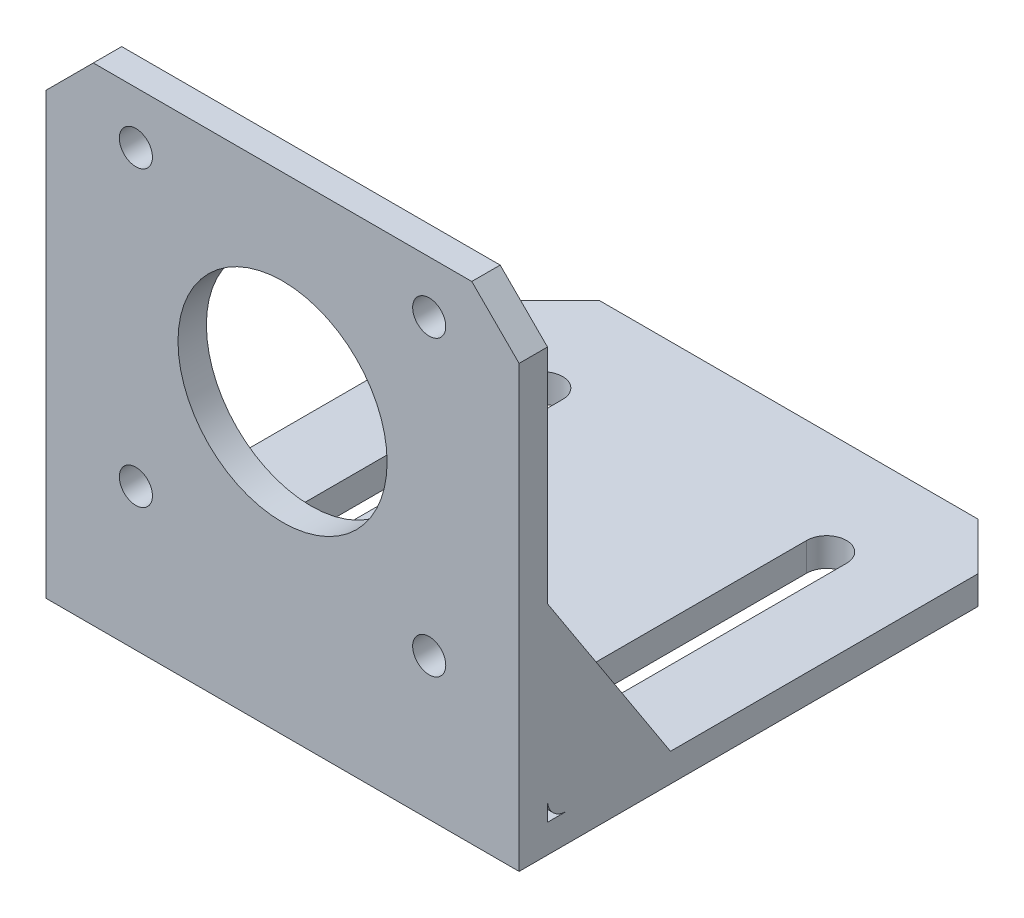
SolidWorks part; units mm, degrees
ref_plane "前视基准面" through (0, 0, 0) normal (0, 0, 1) x (1, 0, 0)
ref_plane "上视基准面" through (0, 0, 0) normal (0, 1, 0) x (1, 0, 0)
ref_plane "右视基准面" through (0, 0, 0) normal (1, 0, 0) x (0, 0, -1)
other "Configuration Table"
sketch "草图1" plane through (0, 0, 0) normal (1, 0, 0) x (0, 0, -1)
  line L0 (0, 0) -> (3, 0)
  line L1 (3, 0) -> (3, -48.5)
  line L2 (3, -48.5) -> (53.5, -48.5)
  line L3 (53.5, -48.5) -> (53.5, -51.5)
  line L4 (53.5, -51.5) -> (0, -51.5)
  line L5 (0, -51.5) -> (0, 0)
  dimension "D1" = 3
  dimension "D2" = 3
  dimension "D3" = 53.5
  dimension "D4" = 51.5
  dimension "D5" = 48.5
extrude "凸台-拉伸1" add sketch "草图1" along normal blind 50
sketch "草图2" plane through (0, 0, -3) normal (0, 0, -1) x (-1, 0, 0)
  line L0 (-50, 0) -> (0, 0) construction
  line L3 (-50, -48.5) -> (-50, 0) construction
  circle A0 centre (-25, -21) radius 11.05
  dimension "D1" = 22.1
  dimension "D2" = 21
  dimension "D3" = 25
extrude "切除-拉伸1" cut sketch "草图2" against normal through all
chamfer "倒角1" distance 5 angle 45 4 edges at (0, -50, -53.5) (50, -50, -53.5) (50, 0, -1.5) (0, 0, -1.5)
sketch "草图3" plane through (0, 0, -3) normal (0, 0, -1) x (-1, 0, 0)
  line L0 (-25, -21) -> (-25, 1.3621) construction
  line L1 (-40.5, -5.5) -> (-40.5, -45.4102) construction
  circle A0 centre (-40.5, -5.5) radius 1.75
  circle A1 centre (-9.5, -5.5) radius 1.75
  circle A2 centre (-9.5, -36.5) radius 1.75
  circle A3 centre (-40.5, -36.5) radius 1.75
  circle A4 centre (-25, -21) radius 21.9203 construction
  point P12 (0, 0)
  dimension "D1" = 3.5
  dimension "D2" = 3.5
  dimension "D3" = 3.5
  dimension "D4" = 3.5
  dimension "D5" = 31
  dimension "D6" = 31
  dimension "D7" = 31
extrude "切除-拉伸2" cut sketch "草图3" against normal through all
sketch "草图4" plane through (50, 0, 0) normal (1, 0, 0) x (0, 0, -1)
  line L0 (3, -28.5) -> (16, -48.5)
  line L1 (3, -48.5) -> (3, -5) construction
  line L2 (48.5, -48.5) -> (3, -48.5) construction
  line L3 (3, -28.5) -> (3, -46.5)
  line L4 (5, -48.5) -> (16, -48.5)
  arc A0 (3, -46.5) -> (5, -48.5) centre (5, -46.5) ccw
  point P10 (3, -48.5)
  dimension "D3" = 2
  dimension "D1" = 20
  dimension "D2" = 13
extrude "凸台-拉伸3" add sketch "草图4" against normal blind 3
sketch "草图5" plane through (0, 0, 0) normal (-1, 0, 0) x (0, 0, 1)
  line L0 (-5, -48.5) -> (-16, -48.5)
  line L1 (-16, -48.5) -> (-3, -28.5)
  line L2 (-3, -28.5) -> (-3, -46.5)
  arc A0 (-5, -48.5) -> (-3, -46.5) centre (-5, -46.5) ccw
  point P8 (-3, -48.5)
  dimension "D1" = 2
extrude "凸台-拉伸4" add sketch "草图5" against normal blind 3
sketch "草图6" plane through (0, -48.5, 0) normal (0, 1, 0) x (1, 0, 0)
  line L0 (10, 42.5) -> (10, 12.5) construction
  line L1 (12.1, 42.5) -> (12.1, 12.5)
  line L2 (7.9, 42.5) -> (7.9, 12.5)
  line L3 (40, 42.5) -> (40, 12.5) construction
  line L4 (42.1, 42.5) -> (42.1, 12.5)
  line L5 (37.9, 42.5) -> (37.9, 12.5)
  line L6 (45, 53.5) -> (5, 53.5) construction
  line L7 (25, 53.5) -> (25, 11.7146) construction
  arc A0 (12.1, 42.5) -> (7.9, 42.5) centre (10, 42.5) ccw
  arc A1 (7.9, 12.5) -> (12.1, 12.5) centre (10, 12.5) ccw
  arc A2 (42.1, 42.5) -> (37.9, 42.5) centre (40, 42.5) ccw
  arc A3 (37.9, 12.5) -> (42.1, 12.5) centre (40, 12.5) ccw
  point P2 (10, 27.5)
  point P9 (40, 27.5)
  point P18 (40.09, 12.5)
  dimension "D2" = 2.1
  dimension "D4" = 2.1
  dimension "D1" = 30
  dimension "D3" = 30
  dimension "D5" = 30
  dimension "D6" = 11
extrude "切除-拉伸3" cut sketch "草图6" against normal through all
